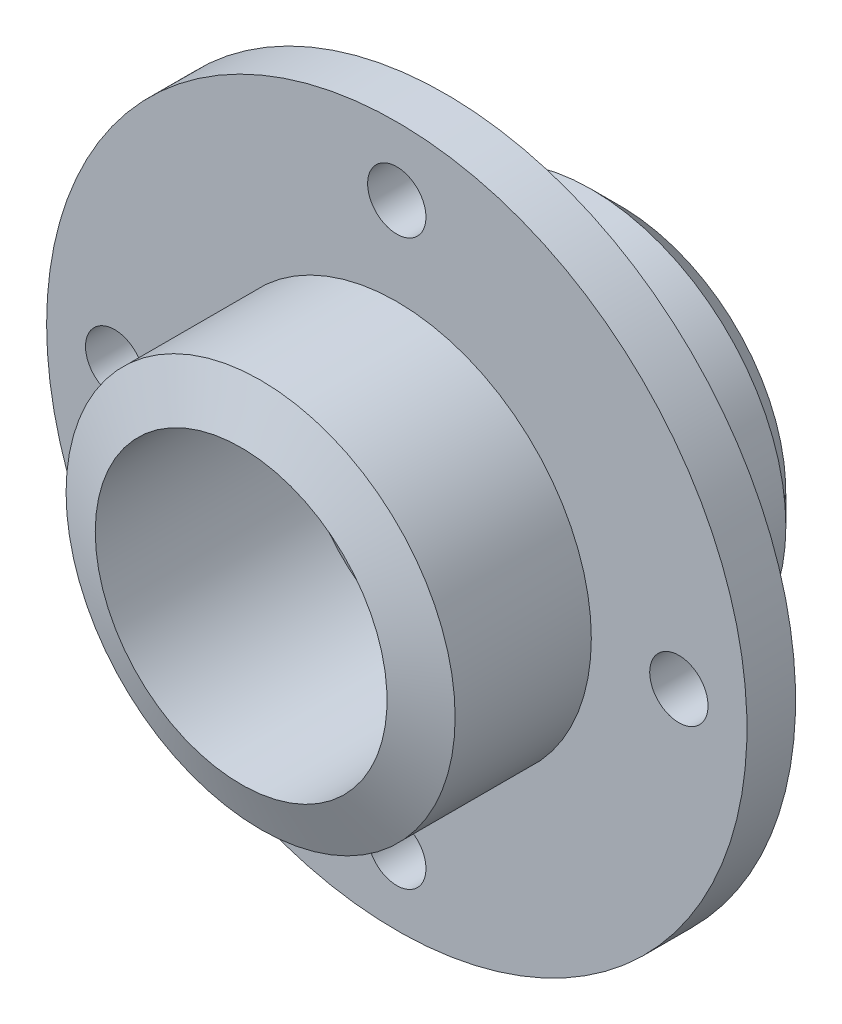
SolidWorks part; units mm, degrees
ref_plane "Front Plane" through (0, 0, 0) normal (0, 0, 1) x (1, 0, 0)
ref_plane "Top Plane" through (0, 0, 0) normal (0, 1, 0) x (1, 0, 0)
ref_plane "Right Plane" through (0, 0, 0) normal (1, 0, 0) x (0, 0, -1)
sketch "Sketch1" plane through (0, 0, 0) normal (0, 1, 0) x (1, 0, 0)
  line L0 (0, 115.8493) -> (0, -51.5745) construction
  line L2 (30, 0) -> (40, 4)
  line L3 (72, 42) -> (72, 32)
  line L4 (40, 4) -> (40, 32)
  line L5 (40, 32) -> (72, 32)
  line L6 (40, 42) -> (72, 42)
  line L7 (40, 42) -> (40, 72)
  line L8 (40, 72) -> (34, 78)
  line L9 (34, 78) -> (0, 78)
  line L10 (30, 0) -> (30, 42)
  line L11 (30, 42) -> (0, 42)
  line L12 (34, 72) -> (34, 45)
  line L13 (30, 42) -> (31, 42)
  line L14 (34, 72) -> (0, 72)
  line L15 (0, 78) -> (0, 72)
  arc A0 (31, 42) -> (34, 45) centre (31, 45) ccw
  dimension "D12" = 6
  dimension "D2" = 40
  dimension "D3" = 4
  dimension "D4" = 144
  dimension "D5" = 32
  dimension "D6" = 10
  dimension "D7" = 30
  dimension "D8" = 6
  dimension "D9" = 34
  dimension "D10" = 36
  dimension "D11" = 6
  dimension "D13" = 30
revolve "Revolve2" add sketch "Sketch1" angle 360 about L0
sketch "Sketch2" plane through (0, 0, -42) normal (0, 0, -1) x (-1, 0, 0)
  line L0 (0, 82.3564) -> (0, -78.0645) construction
  circle A0 centre (58, 0) radius 6
  circle A1 centre (0, -58) radius 6
  circle A2 centre (-58, 0) radius 6
  circle A3 centre (0, 58) radius 6
  point P14 (0, 0)
  dimension "D1" = 12
  dimension "D2" = 58
  dimension "D4" = 58
  dimension "D5" = 58
  dimension "D3" = 4
extrude "Cut-Extrude1" cut sketch "Sketch2" against normal up to surface (10 mm away) up to face at (-72, 0, -32)
sketch "Sketch3" plane through (0, 0, -78) normal (0, 0, -1) x (-1, 0, 0)
  line L0 (0, 75.1832) -> (0, -82.5131) construction
  line L1 (-6, 32) -> (6, 32)
  line L2 (-6, 32) -> (-6, 23.2379)
  line L3 (6, 32) -> (6, 23.2379)
  arc A0 (-6, 23.2379) -> (6, 23.2379) centre (0, 0) ccw
  point P7 (0, 32)
  dimension "D1" = 24
  dimension "D2" = 32
  dimension "D3" = 12
extrude "Cut-Extrude2" cut sketch "Sketch3" against normal blind 6
